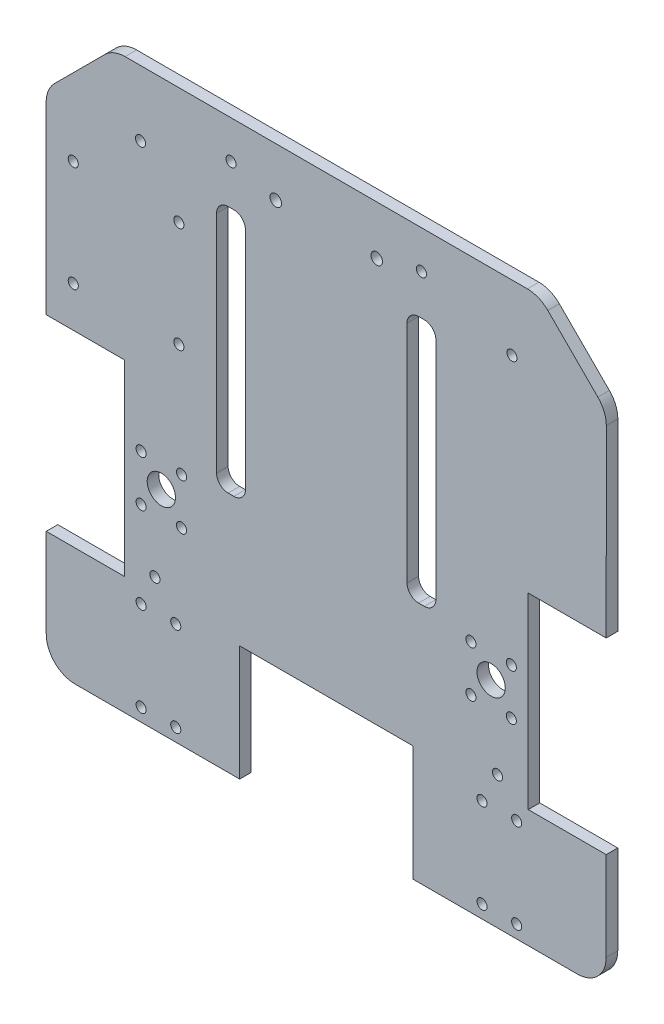
SolidWorks part; units mm, degrees
material "PMMA"
ref_plane "前视基准面" through (0, 0, 0) normal (0, 0, 1) x (1, 0, 0)
ref_plane "上视基准面" through (0, 0, 0) normal (0, 1, 0) x (1, 0, 0)
ref_plane "右视基准面" through (0, 0, 0) normal (1, 0, 0) x (0, 0, -1)
sketch "草图3" plane through (0, 0, 0) normal (0, 0, 1) x (1, 0, 0)
  line L1 (73.5057, 259.0895) -> (196.9372, 259.0895)
  line L2 (25.2215, 210.8052) -> (25.2215, 54.0895)
  line L3 (45.2215, 34.0895) -> (225.2215, 34.0895)
  line L4 (245.2215, 210.8052) -> (245.2215, 54.0895)
  line L6 (31.0793, 224.9474) -> (59.3636, 253.2316)
  line L9 (211.0793, 253.2316) -> (239.3636, 224.9474)
  arc A0 (73.5057, 259.0895) -> (59.3636, 253.2316) centre (73.5057, 239.0895) ccw
  arc A1 (211.0793, 253.2316) -> (196.9372, 259.0895) centre (196.9372, 239.0895) ccw
  arc A2 (31.0793, 224.9474) -> (25.2215, 210.8052) centre (45.2215, 210.8052) ccw
  arc A3 (25.2215, 54.0895) -> (45.2215, 34.0895) centre (45.2215, 54.0895) ccw
  arc A4 (225.2215, 34.0895) -> (245.2215, 54.0895) centre (225.2215, 54.0895) ccw
  arc A5 (245.2215, 210.8052) -> (239.3636, 224.9474) centre (225.2215, 210.8052) ccw
  dimension "D1" = 20
  dimension "D2" = 20
  dimension "D3" = 20
extrude "凸台-拉伸1" add sketch "草图3" along normal blind 4
sketch "电池槽" plane through (0, 0, 0) normal (0, 0, 1) x (1, 0, 0)
  line L0 (135.2215, 259.0895) -> (135.2215, 34.0895) construction
  line L6 (59.3636, 253.2316) -> (31.0793, 224.9474)
  line L7 (25.2215, 210.8052) -> (25.2215, 54.0895)
  line L8 (45.2215, 34.0895) -> (225.2215, 34.0895)
  line L9 (245.2215, 54.0895) -> (245.2215, 210.8052)
  line L10 (239.3636, 224.9474) -> (211.0793, 253.2316)
  line L11 (196.9372, 259.0895) -> (73.5057, 259.0895)
  line L12 (59.3636, 253.2316) -> (31.0793, 224.9474)
  line L13 (25.2215, 210.8052) -> (25.2215, 54.0895)
  line L14 (45.2215, 34.0895) -> (225.2215, 34.0895)
  line L15 (245.2215, 54.0895) -> (245.2215, 210.8052)
  line L16 (239.3636, 224.9474) -> (211.0793, 253.2316)
  line L17 (196.9372, 259.0895) -> (73.5057, 259.0895)
  line L21 (25.2215, 132.4474) -> (245.2215, 132.4474) construction
  line L22 (95.2215, 234.9474) -> (175.2215, 234.9474)
  line L24 (105.2215, 224.9474) -> (165.2215, 224.9474)
  line L25 (105.2215, 224.9474) -> (105.2215, 154.9474)
  line L26 (105.2215, 154.9474) -> (165.2215, 154.9474)
  line L27 (165.2215, 224.9474) -> (165.2215, 154.9474)
  line L28 (105.2215, 224.9474) -> (165.2215, 154.9474) construction
  line L29 (105.2215, 154.9474) -> (165.2215, 224.9474) construction
  line L30 (175.2215, 234.9474) -> (175.2215, 144.9474)
  line L31 (95.2215, 144.9474) -> (175.2215, 144.9474)
  line L32 (95.2215, 234.9474) -> (95.2215, 144.9474)
  line L33 (95.2215, 234.9474) -> (105.2215, 224.9474) construction
  line L34 (105.2215, 154.9474) -> (95.2215, 144.9474) construction
  line L35 (165.2215, 154.9474) -> (175.2215, 144.9474) construction
  line L36 (165.2215, 224.9474) -> (175.2215, 234.9474) construction
  line L37 (97.2215, 232.9474) -> (173.2215, 232.9474)
  line L38 (173.2215, 232.9474) -> (173.2215, 146.9474)
  line L39 (97.2215, 146.9474) -> (173.2215, 146.9474)
  line L40 (97.2215, 232.9474) -> (97.2215, 146.9474)
  arc A6 (73.5057, 259.0895) -> (59.3636, 253.2316) centre (73.5057, 239.0895) ccw
  arc A7 (31.0793, 224.9474) -> (25.2215, 210.8052) centre (45.2215, 210.8052) ccw
  arc A8 (25.2215, 54.0895) -> (45.2215, 34.0895) centre (45.2215, 54.0895) ccw
  arc A9 (225.2215, 34.0895) -> (245.2215, 54.0895) centre (225.2215, 54.0895) ccw
  arc A10 (245.2215, 210.8052) -> (239.3636, 224.9474) centre (225.2215, 210.8052) ccw
  arc A11 (211.0793, 253.2316) -> (196.9372, 259.0895) centre (196.9372, 239.0895) ccw
  arc A12 (73.5057, 259.0895) -> (59.3636, 253.2316) centre (73.5057, 239.0895) ccw
  arc A13 (31.0793, 224.9474) -> (25.2215, 210.8052) centre (45.2215, 210.8052) ccw
  arc A14 (25.2215, 54.0895) -> (45.2215, 34.0895) centre (45.2215, 54.0895) ccw
  arc A15 (225.2215, 34.0895) -> (245.2215, 54.0895) centre (225.2215, 54.0895) ccw
  arc A16 (245.2215, 210.8052) -> (239.3636, 224.9474) centre (225.2215, 210.8052) ccw
  arc A17 (211.0793, 253.2316) -> (196.9372, 259.0895) centre (196.9372, 239.0895) ccw
  circle A20 centre (168.2215, 227.9474) radius 1.75
  circle A21 centre (168.2215, 151.9474) radius 1.75
  circle A22 centre (102.2215, 151.9474) radius 1.75
  circle A23 centre (102.2215, 227.9474) radius 1.75
  point P18 (135.2215, 189.9474)
  dimension "D3" = 8
  dimension "D2" = 10
  dimension "D1" = 0
sketch "轮槽" plane through (0, 0, 4) normal (0, 0, 1) x (1, 0, 0)
  line L2 (235.2215, 149.9474) -> (245.2215, 149.9474)
  line L3 (235.2215, 84.9474) -> (245.2215, 84.9474)
  line L4 (205.2215, 84.9474) -> (235.2215, 84.9474)
  line L5 (25.2215, 149.9474) -> (47.2215, 149.9474)
  line L6 (59.3636, 253.2316) -> (31.0793, 224.9474)
  line L7 (25.2215, 210.8052) -> (25.2215, 54.0895)
  line L8 (45.2215, 34.0895) -> (225.2215, 34.0895)
  line L9 (245.2215, 54.0895) -> (245.2215, 210.8052)
  line L10 (239.3636, 224.9474) -> (211.0793, 253.2316)
  line L11 (196.9372, 259.0895) -> (73.5057, 259.0895)
  line L12 (59.3636, 253.2316) -> (31.0793, 224.9474) construction
  line L13 (25.2215, 210.8052) -> (25.2215, 54.0895) construction
  line L14 (45.2215, 34.0895) -> (225.2215, 34.0895) construction
  line L15 (245.2215, 54.0895) -> (245.2215, 210.8052) construction
  line L16 (239.3636, 224.9474) -> (211.0793, 253.2316) construction
  line L17 (196.9372, 259.0895) -> (73.5057, 259.0895) construction
  line L18 (47.2215, 149.9474) -> (65.2215, 149.9474)
  line L19 (65.2215, 149.9474) -> (65.2215, 84.9474)
  line L20 (65.2215, 84.9474) -> (25.2215, 84.9474)
  line L21 (205.2215, 149.9474) -> (205.2215, 84.9474)
  line L22 (235.2215, 149.9474) -> (223.2215, 149.9474)
  line L23 (223.2215, 149.9474) -> (205.2215, 149.9474)
  arc A6 (73.5057, 259.0895) -> (59.3636, 253.2316) centre (73.5057, 239.0895) ccw
  arc A7 (31.0793, 224.9474) -> (25.2215, 210.8052) centre (45.2215, 210.8052) ccw
  arc A8 (25.2215, 54.0895) -> (45.2215, 34.0895) centre (45.2215, 54.0895) ccw
  arc A9 (225.2215, 34.0895) -> (245.2215, 54.0895) centre (225.2215, 54.0895) ccw
  arc A10 (245.2215, 210.8052) -> (239.3636, 224.9474) centre (225.2215, 210.8052) ccw
  arc A11 (211.0793, 253.2316) -> (196.9372, 259.0895) centre (196.9372, 239.0895) ccw
  arc A12 (73.5057, 259.0895) -> (59.3636, 253.2316) centre (73.5057, 239.0895) ccw construction
  arc A13 (31.0793, 224.9474) -> (25.2215, 210.8052) centre (45.2215, 210.8052) ccw construction
  arc A14 (25.2215, 54.0895) -> (45.2215, 34.0895) centre (45.2215, 54.0895) ccw construction
  arc A15 (225.2215, 34.0895) -> (245.2215, 54.0895) centre (225.2215, 54.0895) ccw construction
  arc A16 (245.2215, 210.8052) -> (239.3636, 224.9474) centre (225.2215, 210.8052) ccw construction
  arc A17 (211.0793, 253.2316) -> (196.9372, 259.0895) centre (196.9372, 239.0895) ccw construction
  line M18 (25.2215, 210.8052) -> (25.2215, 54.0895)
  line M22 (245.2215, 54.0895) -> (245.2215, 210.8052)
  dimension "D1" = 0
sketch "电机" plane through (0, 0, 0) normal (0, 0, 1) x (1, 0, 0)
  line L1 (71.0715, 125.4474) -> (85.0715, 125.4474) construction
  line L7 (65.2215, 130.6974) -> (93.2215, 130.6974) construction
  line L8 (245.2215, 122.9274) -> (237.0715, 122.9274) construction
  line L9 (85.0715, 125.4474) -> (71.0715, 125.4474) construction
  line L26 (93.2215, 130.6974) -> (93.2215, 104.1974) construction
  line L27 (65.2215, 117.4474) -> (33.3715, 117.4474) construction
  line L28 (217.2215, 122.9274) -> (215.3715, 122.9274) construction
  line L29 (215.3715, 122.9274) -> (215.3715, 130.9274) construction
  line L30 (65.2215, 111.9674) -> (65.2215, 104.1974) construction
  line L31 (169.3715, 130.9274) -> (215.3715, 130.9274) construction
  line L32 (192.3715, 130.9274) -> (192.3715, 114.9274) construction
  line L33 (237.0715, 122.9274) -> (215.3715, 122.9274) construction
  line L34 (215.3715, 114.9274) -> (169.3715, 114.9274) construction
  line L35 (135.2215, 259.0895) -> (135.2215, 34.0895) construction
  line L36 (196.9372, 259.0895) -> (73.5057, 259.0895) construction
  line L37 (45.2215, 34.0895) -> (225.2215, 34.0895) construction
  line L39 (85.0715, 117.4474) -> (85.0715, 125.4474) construction
  line L40 (85.0715, 109.4474) -> (71.0715, 109.4474) construction
  line L41 (78.0715, 125.4474) -> (78.0715, 109.4474) construction
  line L44 (65.2215, 111.9674) -> (65.2215, 130.6974) construction
  line L45 (93.2215, 104.1974) -> (65.2215, 104.1974) construction
  line L51 (93.2215, 117.4474) -> (85.0715, 117.4474) construction
  line L53 (205.2215, 117.4474) -> (205.2215, 109.6774) construction
  line L63 (237.0715, 117.4474) -> (185.3715, 117.4474) construction
  line L64 (205.2215, 111.9674) -> (205.2215, 130.6974) construction
  line L65 (177.2215, 130.6974) -> (177.2215, 104.1974)
  line L66 (205.2215, 104.1974) -> (205.2215, 130.6974)
  line L67 (177.2215, 117.4474) -> (185.3715, 117.4474) construction
  line L68 (177.2215, 104.1974) -> (205.2215, 104.1974) construction
  line L69 (205.2215, 111.9674) -> (205.2215, 130.6974) construction
  line L70 (192.3715, 125.4474) -> (192.3715, 109.4474) construction
  line L71 (185.3715, 109.4474) -> (199.3715, 109.4474) construction
  line L72 (185.3715, 117.4474) -> (185.3715, 125.4474) construction
  line L73 (205.2215, 111.9674) -> (205.2215, 104.1974) construction
  line L74 (205.2215, 130.6974) -> (177.2215, 130.6974)
  line L75 (177.2215, 104.1974) -> (205.2215, 104.1974)
  line L76 (205.2215, 117.4474) -> (237.0715, 117.4474) construction
  line L77 (177.2215, 130.6974) -> (177.2215, 104.1974) construction
  line L78 (185.3715, 125.4474) -> (199.3715, 125.4474) construction
  line L79 (205.2215, 130.6974) -> (177.2215, 130.6974) construction
  line L80 (199.3715, 125.4474) -> (185.3715, 125.4474) construction
  line L81 (65.2215, 111.9674) -> (65.2215, 130.6974) construction
  line L82 (33.3715, 117.4474) -> (85.0715, 117.4474) construction
  line L83 (65.2215, 117.4474) -> (65.2215, 109.6774) construction
  line L84 (55.0715, 114.9274) -> (101.0715, 114.9274) construction
  line L85 (33.3715, 122.9274) -> (55.0715, 122.9274) construction
  line L86 (78.0715, 130.9274) -> (78.0715, 114.9274) construction
  line L87 (101.0715, 130.9274) -> (55.0715, 130.9274) construction
  line L88 (55.0715, 122.9274) -> (55.0715, 130.9274) construction
  line L89 (53.2215, 122.9274) -> (55.0715, 122.9274) construction
  line L90 (25.2215, 122.9274) -> (33.3715, 122.9274) construction
  line L91 (93.2215, 104.1974) -> (65.2215, 104.1974)
  line L92 (65.2215, 130.6974) -> (93.2215, 130.6974)
  line L93 (65.2215, 104.1974) -> (65.2215, 130.6974)
  line L94 (93.2215, 130.6974) -> (93.2215, 104.1974)
  line L95 (65.2215, 130.6974) -> (120.2215, 130.6974) construction
  line L96 (120.2215, 130.6974) -> (120.2215, 104.1974) construction
  line L97 (120.2215, 104.1974) -> (93.2215, 104.1974) construction
  circle A27 centre (185.3715, 109.4474) radius 1.75
  circle A28 centre (199.3715, 125.4474) radius 1.75
  circle A29 centre (192.3715, 117.4474) radius 4.9
  circle A30 centre (185.3715, 125.4474) radius 1.75
  circle A31 centre (199.3715, 109.4474) radius 1.75
  circle A32 centre (71.0715, 109.4474) radius 1.75
  circle A33 centre (85.0715, 125.4474) radius 1.75
  circle A34 centre (78.0715, 117.4474) radius 4.9
  circle A35 centre (71.0715, 125.4474) radius 1.75
  circle A36 centre (85.0715, 109.4474) radius 1.75
sketch "L298N" plane through (0, 0, 0) normal (0, 0, 1) x (1, 0, 0)
  line L0 (73.5057, 239.0895) -> (73.5057, 210.8052) construction
  line L1 (45.2215, 210.8052) -> (73.5057, 210.8052) construction
  line L2 (73.5057, 210.8052) -> (73.5057, 181.8052) construction
  line L3 (47.5557, 200.6552) -> (84.1557, 200.6552) construction
  line L4 (44.3557, 203.8552) -> (87.3557, 203.8552)
  line L5 (44.3557, 203.8552) -> (44.3557, 160.8552)
  line L6 (44.3557, 160.8552) -> (87.3557, 160.8552)
  line L7 (87.3557, 203.8552) -> (87.3557, 160.8552)
  line L8 (44.3557, 203.8552) -> (87.3557, 160.8552) construction
  line L9 (44.3557, 160.8552) -> (87.3557, 203.8552) construction
  circle A0 centre (47.5557, 164.0552) radius 1.75
  circle A2 centre (47.5557, 200.6552) radius 1.75
  circle A3 centre (84.1557, 200.6552) radius 1.75
  circle A4 centre (84.1557, 164.0552) radius 1.75
  point P1 (0, 0)
  point P5 (0, 0)
  point P6 (65.8557, 182.3552)
  point P28 (65.8557, 182.3552)
  dimension "D1" = 4
  dimension "D2" = 43
  dimension "D3" = 36.6
extrude "切除-拉伸5" cut sketch "L298N" along normal blind 10 contours A0 | A2 | A4 | A3
extrude "切除-拉伸7" cut sketch "电池槽" along normal blind 10
extrude "切除-拉伸8" cut sketch "轮槽" against normal blind 10 contours L20 L19 L18 L5 M18 | L22 L23 L21 L4 M22
sketch "万向轮" plane through (0, 0, 0) normal (0, 0, 1) x (1, 0, 0)
  line L0 (135.2215, 259.0895) -> (135.2215, 189.0895) construction
  line L1 (196.9372, 259.0895) -> (73.5057, 259.0895) construction
  line L2 (158.7215, 224.0895) -> (111.7215, 224.0895) construction
  line L3 (152.7215, 224.0895) -> (117.7215, 224.0895)
  line L4 (111.7215, 224.0895) -> (125.647, 235.6363)
  line L5 (158.7215, 224.0895) -> (144.796, 235.6363)
  line L6 (158.7215, 224.0895) -> (144.796, 212.5426)
  line L7 (111.7215, 224.0895) -> (125.647, 212.5426)
  circle A0 centre (117.7215, 224.0895) radius 2
  circle A1 centre (152.7215, 224.0895) radius 2
  circle A2 centre (135.2215, 224.0895) radius 13.5
  circle A3 centre (135.2215, 224.0895) radius 15
  point P7 (135.2215, 224.0895)
  point P10 (135.2215, 224.0895)
extrude "切除-拉伸10" cut sketch "万向轮" along normal blind 10
extrude "切除-拉伸3" cut sketch "电机" along normal blind 10
ref_plane "基准面1" through (0, 0, 4) normal (0, 0, 1) x (1, 0, 0)
sketch "草图11" plane through (0, 0, 4) normal (0, 0, 1) x (1, 0, 0)
  line L0 (26.7439, 218.4589) -> (243.6991, 218.4589) construction
  line L1 (65.8521, 132.7742) -> (204.5909, 132.7742) construction
  line L2 (45.2215, 34.0895) -> (225.2215, 34.0895) construction
  line L3 (204.5909, 257.5671) -> (204.5909, 34.0895) construction
  line L4 (25.2215, 54.0895) -> (245.2215, 54.0895) construction
  line L5 (73.254, 90.0895) -> (74.553, 87.8395)
  line L10 (73.4502, 218.4589) -> (72.1511, 220.7089)
  line L11 (72.1511, 220.7089) -> (69.553, 220.7089)
  line L12 (69.553, 220.7089) -> (68.254, 218.4589)
  line L13 (68.254, 218.4589) -> (69.553, 216.2089)
  line L14 (69.553, 216.2089) -> (72.1511, 216.2089)
  line L15 (72.1511, 216.2089) -> (73.4502, 218.4589)
  line L20 (77.1511, 87.8395) -> (78.4502, 90.0895)
  line L21 (77.1511, 92.3395) -> (74.553, 92.3395)
  line L22 (74.553, 87.8395) -> (77.1511, 87.8395)
  line L23 (74.553, 92.3395) -> (73.254, 90.0895)
  line L32 (78.4502, 90.0895) -> (77.1511, 92.3395)
  line L45 (65.8521, 257.5671) -> (65.8521, 34.0895) construction
  line L49 (191.9928, 90.0895) -> (193.2918, 92.3395)
  line L50 (195.8899, 92.3395) -> (197.1889, 90.0895)
  line L51 (195.8899, 87.8395) -> (193.2918, 87.8395)
  line L52 (193.2918, 92.3395) -> (195.8899, 92.3395)
  line L53 (193.2918, 87.8395) -> (191.9928, 90.0895)
  line L54 (198.2918, 216.2089) -> (196.9928, 218.4589)
  line L55 (200.8899, 216.2089) -> (198.2918, 216.2089)
  line L56 (202.1889, 218.4589) -> (200.8899, 216.2089)
  line L57 (200.8899, 220.7089) -> (202.1889, 218.4589)
  line L58 (198.2918, 220.7089) -> (200.8899, 220.7089)
  line L61 (25.2215, 84.9474) -> (25.2215, 54.0895)
  line L62 (45.2215, 34.0895) -> (225.2215, 34.0895)
  line L63 (245.2215, 54.0895) -> (245.2215, 84.9474)
  line L68 (239.3636, 224.9474) -> (211.0793, 253.2316)
  line L69 (196.9372, 259.0895) -> (73.5057, 259.0895)
  line L70 (59.3636, 253.2316) -> (31.0793, 224.9474)
  line L75 (25.2215, 84.9474) -> (25.2215, 54.0895)
  line L76 (45.2215, 34.0895) -> (225.2215, 34.0895)
  line L77 (245.2215, 54.0895) -> (245.2215, 84.9474)
  line L82 (239.3636, 224.9474) -> (211.0793, 253.2316)
  line L83 (196.9372, 259.0895) -> (73.5057, 259.0895)
  line L84 (59.3636, 253.2316) -> (31.0793, 224.9474)
  line L87 (196.9928, 218.4589) -> (198.2918, 220.7089)
  line L88 (197.1889, 90.0895) -> (195.8899, 87.8395)
  line L93 (65.2215, 149.9474) -> (65.2215, 84.9474)
  line L94 (65.2215, 149.9474) -> (65.2215, 84.9474)
  line L95 (65.2215, 84.9474) -> (25.2215, 84.9474)
  line L96 (65.2215, 84.9474) -> (25.2215, 84.9474)
  line L97 (245.2215, 84.9474) -> (205.2215, 84.9474)
  line L98 (245.2215, 84.9474) -> (205.2215, 84.9474)
  line L99 (205.2215, 84.9474) -> (205.2215, 149.9474)
  line L100 (205.2215, 84.9474) -> (205.2215, 149.9474)
  line L101 (205.2215, 149.9474) -> (245.2215, 149.9474)
  line L102 (205.2215, 149.9474) -> (245.2215, 149.9474)
  line L103 (245.2215, 149.9474) -> (245.2215, 210.8052)
  line L104 (245.2215, 149.9474) -> (245.2215, 210.8052)
  line L105 (25.2215, 210.8052) -> (25.2215, 149.9474)
  line L106 (25.2215, 210.8052) -> (25.2215, 149.9474)
  line L107 (25.2215, 149.9474) -> (65.2215, 149.9474)
  line L108 (25.2215, 149.9474) -> (65.2215, 149.9474)
  arc A0 (31.0793, 224.9474) -> (25.2215, 210.8052) centre (45.2215, 210.8052) ccw construction
  arc A1 (245.2215, 210.8052) -> (239.3636, 224.9474) centre (225.2215, 210.8052) ccw construction
  circle A2 centre (75.8521, 90.0895) radius 1.75
  arc A3 (211.0793, 253.2316) -> (196.9372, 259.0895) centre (196.9372, 239.0895) ccw construction
  arc A4 (25.2215, 54.0895) -> (45.2215, 34.0895) centre (45.2215, 54.0895) ccw construction
  circle A9 centre (70.8521, 218.4589) radius 1.75
  circle A12 centre (199.5909, 218.4589) radius 1.75
  circle A13 centre (194.5909, 90.0895) radius 1.75
  arc A18 (25.2215, 54.0895) -> (45.2215, 34.0895) centre (45.2215, 54.0895) ccw
  arc A19 (225.2215, 34.0895) -> (245.2215, 54.0895) centre (225.2215, 54.0895) ccw
  arc A20 (245.2215, 210.8052) -> (239.3636, 224.9474) centre (225.2215, 210.8052) ccw
  arc A21 (211.0793, 253.2316) -> (196.9372, 259.0895) centre (196.9372, 239.0895) ccw
  arc A22 (73.5057, 259.0895) -> (59.3636, 253.2316) centre (73.5057, 239.0895) ccw
  arc A23 (31.0793, 224.9474) -> (25.2215, 210.8052) centre (45.2215, 210.8052) ccw
  arc A24 (25.2215, 54.0895) -> (45.2215, 34.0895) centre (45.2215, 54.0895) ccw
  arc A25 (225.2215, 34.0895) -> (245.2215, 54.0895) centre (225.2215, 54.0895) ccw
  arc A26 (245.2215, 210.8052) -> (239.3636, 224.9474) centre (225.2215, 210.8052) ccw
  arc A27 (211.0793, 253.2316) -> (196.9372, 259.0895) centre (196.9372, 239.0895) ccw
  arc A28 (73.5057, 259.0895) -> (59.3636, 253.2316) centre (73.5057, 239.0895) ccw
  arc A29 (31.0793, 224.9474) -> (25.2215, 210.8052) centre (45.2215, 210.8052) ccw
  dimension "D1" = 4.5
  dimension "D3" = 36
  dimension "D2" = 0
extrude "切除-拉伸11" cut sketch "草图11" against normal up to next contours A9 | A2 | A13 | A12
ref_plane "基准面2" through (0, 0, 4) normal (0, 0, 1) x (1, 0, 0)
sketch "草图12" plane through (0, 0, 4) normal (0, 0, 1) x (1, 0, 0)
  line L0 (105.2215, 34.0895) -> (165.2215, 34.0895)
  line L1 (165.2215, -5.9105) -> (105.2215, -5.9105)
  line L2 (165.2215, -5.9105) -> (165.2215, 74.0895)
  line L3 (165.2215, 74.0895) -> (105.2215, 74.0895)
  line L4 (105.2215, -5.9105) -> (105.2215, 74.0895)
  line L5 (165.2215, -5.9105) -> (105.2215, 74.0895) construction
  line L6 (165.2215, 74.0895) -> (105.2215, -5.9105) construction
  line L7 (105.2215, 74.0895) -> (105.2215, 84.0895)
  line L8 (105.2215, 84.0895) -> (165.2215, 84.0895)
  line L9 (165.2215, 84.0895) -> (165.2215, 74.0895)
  point P0 (135.2215, 34.0895)
extrude "切除-拉伸12" cut sketch "草图12" against normal blind 10 contours L4 L0 L2 L3 | L9 L8 L7 L3
sketch "草图13" plane through (0, 0, 4) normal (0, 0, 1) x (1, 0, 0)
  line L0 (105.2215, 44.0895) -> (93.5715, 44.0895) construction
  line L1 (105.2215, 44.0895) -> (105.2215, 84.0895) construction
  line L3 (93.5715, 44.0895) -> (84.7215, 44.0895) construction
  line L4 (84.7215, 44.0895) -> (81.4215, 44.0895) construction
  line L5 (81.4215, 44.0895) -> (72.7215, 44.0895) construction
  line L6 (72.7215, 44.0895) -> (69.4215, 44.0895) construction
  line L9 (105.2215, 48.5895) -> (58.9496, 48.5895) construction
  line L10 (105.2215, 84.0895) -> (83.0715, 84.0895) construction
  line L11 (83.0715, 84.0895) -> (71.0715, 84.0895) construction
  line L12 (105.2215, 64.0895) -> (57.599, 64.0895) construction
  line L13 (165.2215, 64.0895) -> (224.665, 64.0895) construction
  line L16 (189.2215, 79.5895) -> (201.2215, 79.5895) construction
  line L17 (165.2215, 84.0895) -> (165.2215, 79.5895) construction
  line L18 (165.2215, 79.5895) -> (201.2215, 79.5895) construction
  circle A0 centre (83.0715, 48.5895) radius 1.75
  circle A1 centre (71.0715, 48.5895) radius 1.75
  circle A2 centre (71.0715, 79.5895) radius 1.75
  circle A3 centre (83.0715, 79.5895) radius 1.75
  circle A4 centre (189.2215, 79.5895) radius 1.75
  circle A5 centre (201.2215, 79.5895) radius 1.75
  circle A6 centre (201.2215, 48.5895) radius 1.75
  circle A7 centre (189.2215, 48.5895) radius 1.75
extrude "切除-拉伸14" cut sketch "草图13" against normal through all
sketch "草图14" plane through (0, 0, 4) normal (0, 0, 1) x (1, 0, 0)
  line L0 (168.2215, 207.9474) -> (163.2215, 207.9474) construction
  line L1 (163.2215, 207.9474) -> (163.2215, 213.9474) construction
  line L2 (163.2215, 213.9474) -> (167.2215, 213.9474) construction
  line L3 (167.2215, 213.9474) -> (169.2215, 213.9474)
  line L4 (173.2215, 209.9474) -> (173.2215, 131.9474)
  line L5 (169.2215, 127.9474) -> (167.2215, 127.9474)
  line L6 (163.2215, 131.9474) -> (163.2215, 209.9474)
  line L9 (107.2215, 213.9474) -> (103.2215, 213.9474) construction
  line L10 (107.2215, 207.9474) -> (107.2215, 213.9474) construction
  line L11 (107.2215, 131.9474) -> (107.2215, 209.9474)
  line L12 (101.2215, 127.9474) -> (103.2215, 127.9474)
  line L13 (97.2215, 209.9474) -> (97.2215, 131.9474)
  line L14 (103.2215, 213.9474) -> (101.2215, 213.9474)
  line L15 (97.2215, 209.9474) -> (107.2215, 209.9474) construction
  line L16 (102.2215, 207.9474) -> (102.2215, 209.9474) construction
  line L17 (168.2215, 207.9474) -> (168.2215, 209.9474) construction
  line L18 (167.2215, 209.9474) -> (169.2215, 209.9474) construction
  arc A0 (169.2215, 213.9474) -> (173.2215, 209.9474) centre (169.2215, 209.9474) cw
  arc A1 (167.2215, 127.9474) -> (163.2215, 131.9474) centre (167.2215, 131.9474) cw
  arc A2 (169.2215, 127.9474) -> (173.2215, 131.9474) centre (169.2215, 131.9474) ccw
  arc A3 (167.2215, 213.9474) -> (163.2215, 209.9474) centre (167.2215, 209.9474) ccw
  arc A4 (103.2215, 213.9474) -> (107.2215, 209.9474) centre (103.2215, 209.9474) cw
  arc A5 (101.2215, 127.9474) -> (97.2215, 131.9474) centre (101.2215, 131.9474) cw
  arc A6 (103.2215, 127.9474) -> (107.2215, 131.9474) centre (103.2215, 131.9474) ccw
  arc A7 (101.2215, 213.9474) -> (97.2215, 209.9474) centre (101.2215, 209.9474) ccw
  circle A9 centre (102.2215, 207.9474) radius 1.75
  dimension "D1" = 4
extrude "切除-拉伸15" cut sketch "草图14" against normal blind 10 contours L14 A7 L13 A5 L12 A6 L11 A4 | L3 A3 L6 A1 L5 A2 L4 A0 | A9
sketch "草图15" plane through (0, 0, 0) normal (0, 0, 1) x (1, 0, 0)
  line L0 (25.2215, 84.9474) -> (38.2215, 84.9474)
  line L2 (58.4347, 238.1606) -> (41.0816, 220.8074)
  line L12 (48.2215, 44.0895) -> (95.2215, 44.0895)
  line L13 (95.2215, 44.0895) -> (95.2215, 84.0895)
  line L14 (95.2215, 84.0895) -> (175.2215, 84.0895)
  line L15 (175.2215, 84.0895) -> (175.2215, 44.0895)
  line L16 (175.2215, 44.0895) -> (222.2215, 44.0895)
  line L22 (229.3614, 220.8074) -> (212.0083, 238.1606)
  line L23 (232.2215, 84.9474) -> (245.2215, 84.9474)
  line L30 (232.2562, 149.9474) -> (245.2215, 149.9474)
  line L32 (25.2215, 149.9474) -> (38.1867, 149.9474)
  line L35 (65.5057, 241.0895) -> (204.9372, 241.0895)
  line L63 (38.2215, 74.9474) -> (38.2215, 84.9474)
  line L64 (38.2215, 74.9474) -> (38.2215, 54.0895)
  line L79 (178.2215, 47.0895) -> (225.2215, 47.0895) construction
  line L82 (232.2215, 54.0895) -> (232.2215, 74.9474)
  line L83 (232.2215, 74.9474) -> (232.2215, 84.9474)
  line L102 (38.1867, 149.9474) -> (38.1526, 213.731)
  line L103 (232.2562, 149.9474) -> (232.2903, 213.731)
  line L105 (45.2215, 47.0895) -> (92.2215, 47.0895) construction
  line L106 (92.2215, 87.0895) -> (178.2215, 87.0895) construction
  line L114 (45.2215, 44.0895) -> (95.2215, 44.0895) construction
  line L116 (38.2215, 74.9474) -> (38.2215, 54.0895) construction
  line L118 (175.2215, 44.0895) -> (225.2215, 44.0895) construction
  line L122 (232.2215, 54.0895) -> (232.2215, 74.9474) construction
  line L145 (45.2215, 34.0895) -> (105.2215, 34.0895)
  line L150 (105.2215, 34.0895) -> (105.2215, 84.0895)
  line L151 (105.2215, 84.0895) -> (165.2215, 84.0895)
  line L152 (165.2215, 84.0895) -> (165.2215, 34.0895)
  line L153 (165.2215, 34.0895) -> (225.2215, 34.0895)
  line L158 (245.2215, 54.0895) -> (245.2215, 84.9474)
  line L159 (245.2215, 84.9474) -> (205.2215, 84.9474)
  line L160 (205.2215, 84.9474) -> (205.2215, 149.9474)
  line L162 (205.2215, 149.9474) -> (245.2215, 149.9474)
  line L172 (245.2215, 149.9474) -> (245.2215, 210.8052)
  line L173 (239.3636, 224.9474) -> (211.0793, 253.2316)
  line L180 (196.9372, 259.0895) -> (73.5057, 259.0895)
  line L181 (59.3636, 253.2316) -> (31.0793, 224.9474)
  line L190 (25.2215, 210.8052) -> (25.2215, 149.9474)
  line L191 (25.2215, 149.9474) -> (65.2215, 149.9474)
  line L192 (65.2215, 149.9474) -> (65.2215, 84.9474)
  line L193 (65.2215, 84.9474) -> (25.2215, 84.9474)
  line L194 (25.2215, 84.9474) -> (25.2215, 54.0895)
  line L200 (45.2215, 34.0895) -> (105.2215, 34.0895)
  line L204 (105.2215, 34.0895) -> (105.2215, 84.0895)
  line L205 (105.2215, 84.0895) -> (165.2215, 84.0895)
  line L206 (165.2215, 84.0895) -> (165.2215, 34.0895)
  line L207 (165.2215, 34.0895) -> (225.2215, 34.0895)
  line L212 (245.2215, 54.0895) -> (245.2215, 84.9474)
  line L220 (245.2215, 149.9474) -> (245.2215, 210.8052)
  line L221 (239.3636, 224.9474) -> (211.0793, 253.2316)
  line L222 (196.9372, 259.0895) -> (73.5057, 259.0895)
  line L223 (59.3636, 253.2316) -> (31.0793, 224.9474)
  line L228 (25.2215, 210.8052) -> (25.2215, 149.9474)
  line L236 (35.2215, 74.9474) -> (35.2215, 54.0895) construction
  line L237 (35.2215, 74.9474) -> (35.2215, 84.9474) construction
  line L238 (92.2215, 47.0895) -> (92.2215, 87.0895) construction
  line L239 (178.2215, 87.0895) -> (178.2215, 47.0895) construction
  line L240 (235.2215, 54.0895) -> (235.2215, 74.9474) construction
  line L241 (235.2215, 74.9474) -> (235.2215, 84.9474) construction
  line L242 (25.2215, 84.9474) -> (25.2215, 54.0895)
  arc A22 (204.9372, 241.0895) -> (212.0083, 238.1606) centre (204.9372, 231.0895) cw
  arc A24 (65.5057, 241.0895) -> (58.4347, 238.1606) centre (65.5057, 231.0895) ccw
  arc A27 (48.2215, 44.0895) -> (38.2215, 54.0895) centre (48.2215, 54.0895) cw
  arc A29 (222.2215, 44.0895) -> (232.2215, 54.0895) centre (222.2215, 54.0895) ccw
  arc A31 (232.2903, 213.731) -> (229.3614, 220.8074) centre (222.2903, 213.7364) ccw
  arc A45 (38.1526, 213.731) -> (41.0816, 220.8074) centre (48.1526, 213.7364) cw
  arc A69 (225.2215, 34.0895) -> (245.2215, 54.0895) centre (225.2215, 54.0895) ccw
  arc A71 (245.2215, 210.8052) -> (239.3636, 224.9474) centre (225.2215, 210.8052) ccw
  arc A73 (211.0793, 253.2316) -> (196.9372, 259.0895) centre (196.9372, 239.0895) ccw
  arc A77 (73.5057, 259.0895) -> (59.3636, 253.2316) centre (73.5057, 239.0895) ccw
  arc A81 (31.0793, 224.9474) -> (25.2215, 210.8052) centre (45.2215, 210.8052) ccw
  arc A85 (25.2215, 54.0895) -> (45.2215, 34.0895) centre (45.2215, 54.0895) ccw
  arc A89 (225.2215, 34.0895) -> (245.2215, 54.0895) centre (225.2215, 54.0895) ccw
  arc A93 (245.2215, 210.8052) -> (239.3636, 224.9474) centre (225.2215, 210.8052) ccw
  arc A95 (211.0793, 253.2316) -> (196.9372, 259.0895) centre (196.9372, 239.0895) ccw
  arc A96 (73.5057, 259.0895) -> (59.3636, 253.2316) centre (73.5057, 239.0895) ccw
  arc A97 (31.0793, 224.9474) -> (25.2215, 210.8052) centre (45.2215, 210.8052) ccw
  arc A98 (25.2215, 54.0895) -> (45.2215, 34.0895) centre (45.2215, 54.0895) ccw
  arc A115 (35.2215, 54.0895) -> (45.2215, 44.0895) centre (45.2215, 54.0895) ccw construction
  arc A116 (225.2215, 47.0895) -> (232.2215, 54.0895) centre (225.2215, 54.0895) ccw construction
  arc A117 (38.2215, 54.0895) -> (45.2215, 47.0895) centre (45.2215, 54.0895) ccw construction
  arc A118 (225.2215, 44.0895) -> (235.2215, 54.0895) centre (225.2215, 54.0895) ccw construction
  point P32 (215.2215, 149.9474)
  point P38 (65.2215, 159.9474)
  point P40 (65.2215, 74.9474)
  point P58 (55.2215, 149.9474)
  point P60 (55.2215, 84.9474)
  point P63 (205.2215, 74.9474)
  point P65 (205.2215, 159.9474)
  dimension "D2" = 10
  dimension "D6" = 10
  dimension "D1" = 0
sketch "草图16" plane through (0, 0, 0) normal (0, 0, 1) x (1, 0, 0)
  line L12 (38.1867, 149.9474) -> (38.1526, 213.731)
  line L13 (41.0816, 220.8074) -> (58.4347, 238.1606)
  line L14 (65.5057, 241.0895) -> (204.9372, 241.0895)
  line L15 (212.0083, 238.1606) -> (229.3614, 220.8074)
  line L16 (232.2903, 213.731) -> (232.2562, 149.9474)
  line L17 (232.2562, 149.9474) -> (245.2215, 149.9474)
  line L18 (245.2215, 149.9474) -> (245.2215, 210.8052)
  line L19 (239.3636, 224.9474) -> (211.0793, 253.2316)
  line L20 (196.9372, 259.0895) -> (73.5057, 259.0895)
  line L21 (59.3636, 253.2316) -> (31.0793, 224.9474)
  line L22 (25.2215, 210.8052) -> (25.2215, 149.9474)
  line L23 (25.2215, 149.9474) -> (38.1867, 149.9474)
  line L24 (38.1867, 149.9474) -> (38.1526, 213.731)
  line L25 (41.0816, 220.8074) -> (58.4347, 238.1606)
  line L26 (65.5057, 241.0895) -> (204.9372, 241.0895)
  line L27 (212.0083, 238.1606) -> (229.3614, 220.8074)
  line L28 (232.2903, 213.731) -> (232.2562, 149.9474)
  line L29 (232.2562, 149.9474) -> (245.2215, 149.9474)
  line L30 (245.2215, 149.9474) -> (245.2215, 210.8052)
  line L31 (239.3636, 224.9474) -> (211.0793, 253.2316)
  line L32 (196.9372, 259.0895) -> (73.5057, 259.0895)
  line L33 (59.3636, 253.2316) -> (31.0793, 224.9474)
  line L34 (25.2215, 210.8052) -> (25.2215, 149.9474)
  line L35 (25.2215, 149.9474) -> (38.1867, 149.9474)
  arc A8 (41.0816, 220.8074) -> (38.1526, 213.731) centre (48.1526, 213.7364) ccw
  arc A9 (65.5057, 241.0895) -> (58.4347, 238.1606) centre (65.5057, 231.0895) ccw
  arc A10 (212.0083, 238.1606) -> (204.9372, 241.0895) centre (204.9372, 231.0895) ccw
  arc A11 (232.2903, 213.731) -> (229.3614, 220.8074) centre (222.2903, 213.7364) ccw
  arc A12 (245.2215, 210.8052) -> (239.3636, 224.9474) centre (225.2215, 210.8052) ccw
  arc A13 (211.0793, 253.2316) -> (196.9372, 259.0895) centre (196.9372, 239.0895) ccw
  arc A14 (73.5057, 259.0895) -> (59.3636, 253.2316) centre (73.5057, 239.0895) ccw
  arc A15 (31.0793, 224.9474) -> (25.2215, 210.8052) centre (45.2215, 210.8052) ccw
  arc A16 (41.0816, 220.8074) -> (38.1526, 213.731) centre (48.1526, 213.7364) ccw
  arc A17 (65.5057, 241.0895) -> (58.4347, 238.1606) centre (65.5057, 231.0895) ccw
  arc A18 (212.0083, 238.1606) -> (204.9372, 241.0895) centre (204.9372, 231.0895) ccw
  arc A19 (232.2903, 213.731) -> (229.3614, 220.8074) centre (222.2903, 213.7364) ccw
  arc A20 (245.2215, 210.8052) -> (239.3636, 224.9474) centre (225.2215, 210.8052) ccw
  arc A21 (211.0793, 253.2316) -> (196.9372, 259.0895) centre (196.9372, 239.0895) ccw
  arc A22 (73.5057, 259.0895) -> (59.3636, 253.2316) centre (73.5057, 239.0895) ccw
  arc A23 (31.0793, 224.9474) -> (25.2215, 210.8052) centre (45.2215, 210.8052) ccw
  dimension "D1" = 0
extrude "切除-拉伸16" cut sketch "草图16" along normal blind 10
sketch "草图18" plane through (0, 0, 0) normal (0, 0, 1) x (1, 0, 0)
  line L0 (175.2215, 44.0895) -> (225.2215, 44.0895) construction
  line L1 (48.1867, 44.0895) -> (95.2215, 44.0895)
  line L4 (175.2215, 44.0895) -> (222.2562, 44.0895)
  line L5 (45.2215, 44.0895) -> (95.2215, 44.0895) construction
  line L6 (232.2562, 84.9474) -> (245.2215, 84.9474)
  line L8 (38.1867, 84.9474) -> (38.1867, 54.0895)
  line L10 (232.2562, 84.9474) -> (232.2562, 54.0895)
  line L11 (95.2215, 44.0895) -> (105.2215, 44.0895)
  line L12 (175.2215, 44.0895) -> (165.2215, 44.0895)
  line L14 (105.2215, 34.0895) -> (105.2215, 84.0895) construction
  line L15 (165.2215, 84.0895) -> (165.2215, 34.0895) construction
  line L18 (38.1526, 213.731) -> (38.1867, 149.9474)
  line L19 (38.1867, 149.9474) -> (65.2215, 149.9474)
  line L20 (65.2215, 149.9474) -> (65.2215, 84.9474)
  line L21 (65.2215, 84.9474) -> (25.2215, 84.9474)
  line L22 (25.2215, 84.9474) -> (25.2215, 54.0895)
  line L23 (45.2215, 34.0895) -> (105.2215, 34.0895)
  line L24 (105.2215, 34.0895) -> (105.2215, 84.0895)
  line L25 (105.2215, 84.0895) -> (165.2215, 84.0895)
  line L26 (165.2215, 84.0895) -> (165.2215, 34.0895)
  line L27 (165.2215, 34.0895) -> (225.2215, 34.0895)
  line L28 (245.2215, 54.0895) -> (245.2215, 84.9474)
  line L29 (245.2215, 84.9474) -> (205.2215, 84.9474)
  line L30 (205.2215, 84.9474) -> (205.2215, 149.9474)
  line L31 (205.2215, 149.9474) -> (232.2562, 149.9474)
  line L32 (232.2562, 149.9474) -> (232.2903, 213.731)
  line L33 (229.3614, 220.8074) -> (212.0083, 238.1606)
  line L34 (204.9372, 241.0895) -> (65.5057, 241.0895)
  line L35 (58.4347, 238.1606) -> (41.0816, 220.8074)
  line L39 (38.1867, 84.9474) -> (25.2215, 84.9474)
  line L40 (25.2215, 84.9474) -> (25.2215, 54.0895)
  line L41 (45.2215, 34.0895) -> (105.2215, 34.0895)
  line L42 (105.2215, 34.0895) -> (105.2215, 44.0895)
  line L44 (165.2215, 44.0895) -> (165.2215, 34.0895)
  line L45 (165.2215, 34.0895) -> (225.2215, 34.0895)
  line L46 (245.2215, 54.0895) -> (245.2215, 84.9474)
  line L62 (235.2215, 54.0895) -> (235.2215, 84.9474) construction
  line L63 (35.2215, 84.9474) -> (35.2215, 54.0895) construction
  line L69 (95.2215, 44.0895) -> (95.2215, 84.0895) construction
  line L70 (175.2215, 84.0895) -> (175.2215, 44.0895) construction
  arc A0 (222.2562, 44.0895) -> (232.2562, 54.0895) centre (222.2562, 54.0895) ccw
  arc A1 (48.1867, 44.0895) -> (38.1867, 54.0895) centre (48.1867, 54.0895) cw
  arc A6 (41.0816, 220.8074) -> (38.1526, 213.731) centre (48.1526, 213.7364) ccw
  arc A7 (25.2215, 54.0895) -> (45.2215, 34.0895) centre (45.2215, 54.0895) ccw
  arc A8 (225.2215, 34.0895) -> (245.2215, 54.0895) centre (225.2215, 54.0895) ccw
  arc A9 (232.2903, 213.731) -> (229.3614, 220.8074) centre (222.2903, 213.7364) ccw
  arc A10 (212.0083, 238.1606) -> (204.9372, 241.0895) centre (204.9372, 231.0895) ccw
  arc A11 (65.5057, 241.0895) -> (58.4347, 238.1606) centre (65.5057, 231.0895) ccw
  arc A13 (25.2215, 54.0895) -> (45.2215, 34.0895) centre (45.2215, 54.0895) ccw
  arc A14 (225.2215, 34.0895) -> (245.2215, 54.0895) centre (225.2215, 54.0895) ccw
  arc A20 (225.2215, 44.0895) -> (235.2215, 54.0895) centre (225.2215, 54.0895) ccw construction
  arc A21 (35.2215, 54.0895) -> (45.2215, 44.0895) centre (45.2215, 54.0895) ccw construction
  dimension "D3" = 10
  dimension "D1" = 0
  dimension "D2" = 10
extrude "切除-拉伸17" cut sketch "草图18" along normal blind 10
